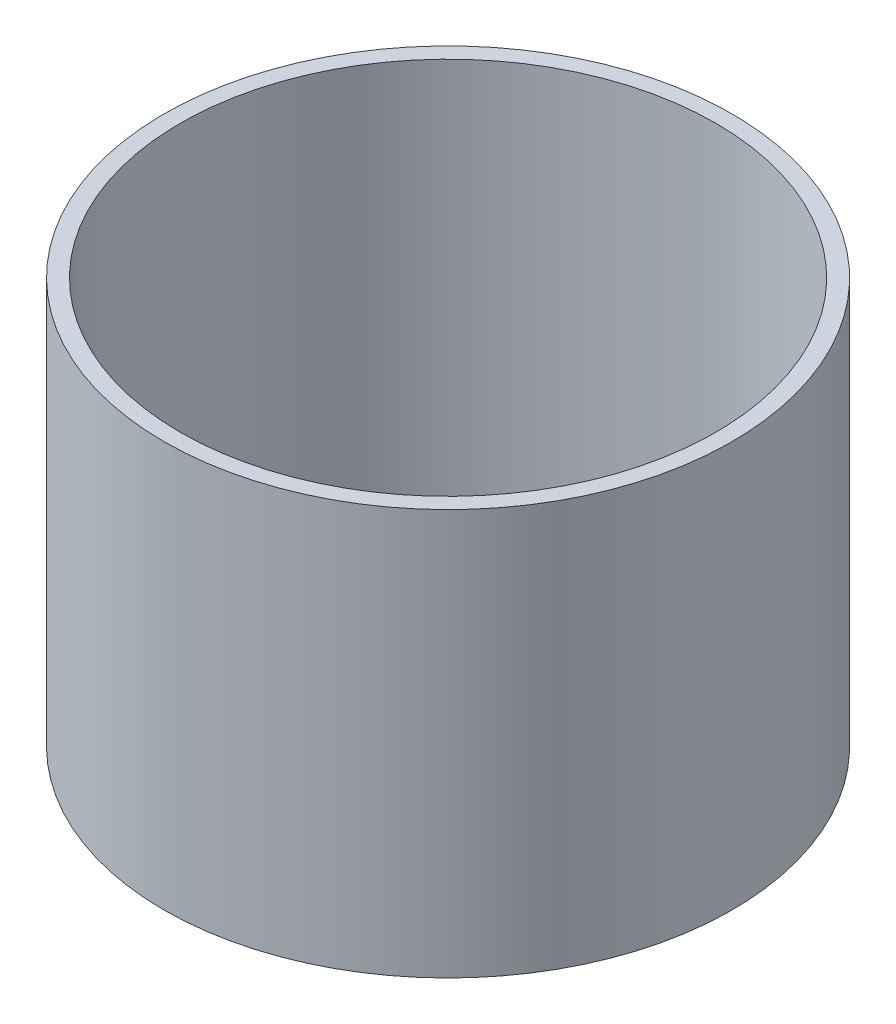
SolidWorks part; units mm, degrees
ref_plane "Front Plane" through (0, 0, 0) normal (0, 0, 1) x (1, 0, 0)
ref_plane "Top Plane" through (0, 0, 0) normal (0, 1, 0) x (1, 0, 0)
ref_plane "Right Plane" through (0, 0, 0) normal (1, 0, 0) x (0, 0, -1)
sketch "Sketch1" plane through (0, 0, 0) normal (0, 1, 0) x (1, 0, 0)
  circle A1 centre (0, 0) radius 16.5
  circle A2 centre (0, 0) radius 17.5
  dimension "D1" = 33
  dimension "D2" = 1
extrude "Boss-Extrude1" add sketch "Sketch1" along normal blind 25
